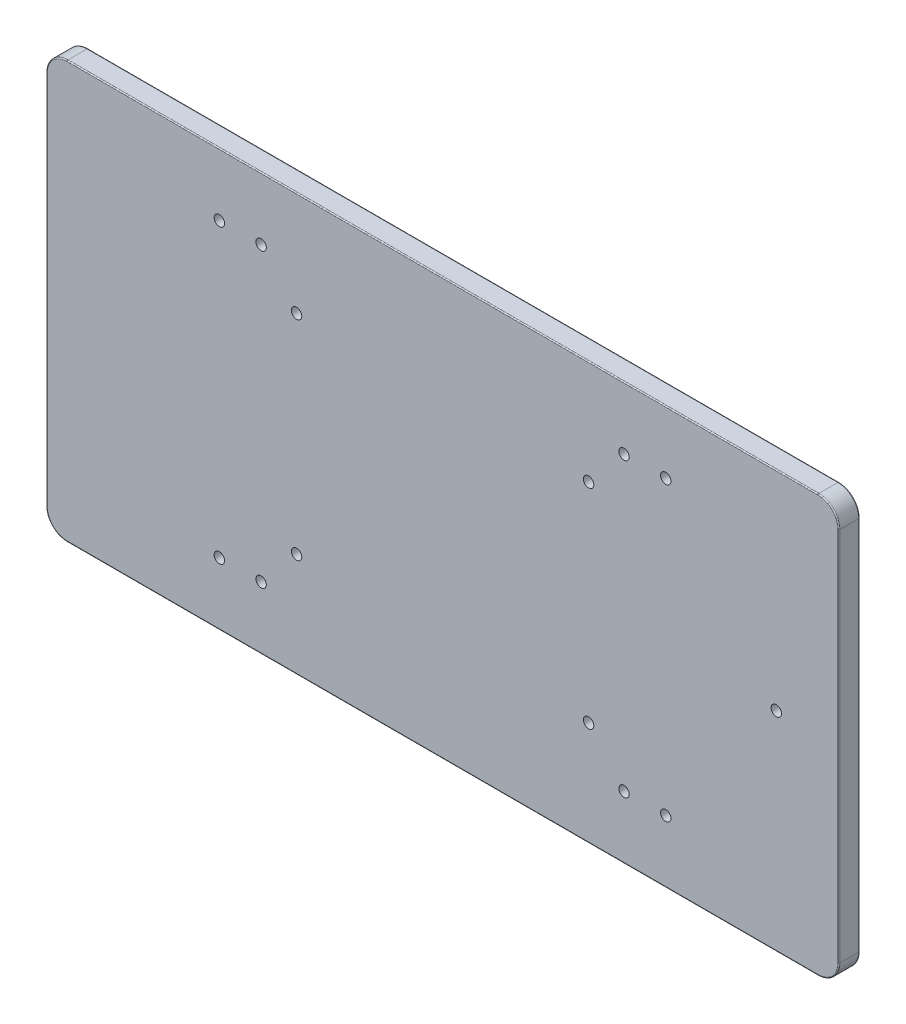
SolidWorks part; units mm, degrees
ref_plane "Front Plane" through (0, 0, 0) normal (0, 0, 1) x (1, 0, 0)
ref_plane "Top Plane" through (0, 0, 0) normal (0, 1, 0) x (1, 0, 0)
ref_plane "Right Plane" through (0, 0, 0) normal (1, 0, 0) x (0, 0, -1)
sketch "Sketch1" plane through (0, 0, 0) normal (0, 0, 1) x (1, 0, 0)
  line L0 (0, 0) -> (30.9738, 0) construction
  line L1 (95, 50) -> (-95, 50)
  line L2 (95, 50) -> (95, -50)
  line L3 (95, -50) -> (-95, -50)
  line L4 (-95, 50) -> (-95, -50)
  line L5 (95, 50) -> (-95, -50) construction
  line L6 (95, -50) -> (-95, 50) construction
  line L7 (-35, 25) -> (35, 25) construction
  line L8 (-35, 25) -> (-35, -25) construction
  line L9 (-35, -25) -> (35, -25) construction
  line L10 (35, 25) -> (35, -25) construction
  line L11 (-35, 25) -> (35, -25) construction
  line L12 (-35, -25) -> (35, 25) construction
  line L13 (30.9738, 0) -> (0, 0) construction
  line L14 (0, 19.8291) -> (0, 0) construction
  line L15 (80, 50) -> (80, -50) construction
  circle A0 centre (-43.5, -35) radius 1.25
  circle A1 centre (-53.5, -35) radius 1.25
  circle A2 centre (-35, -25) radius 1.25
  circle A3 centre (-35, 25) radius 1.25
  circle A4 centre (35, 25) radius 1.25
  circle A5 centre (35, -25) radius 1.25
  circle A6 centre (43.5, -35) radius 1.25
  circle A7 centre (53.5, -35) radius 1.25
  circle A8 centre (53.5, 35) radius 1.25
  circle A9 centre (43.5, 35) radius 1.25
  circle A10 centre (-53.5, 35) radius 1.25
  circle A11 centre (-43.5, 35) radius 1.25
  circle A12 centre (80, 0) radius 1.25
  point P0 (0, 0)
  point P6 (0, 0)
  dimension "D7" = 2.5
  dimension "D10" = 2.5
  dimension "D1" = 190
  dimension "D2" = 100
  dimension "D3" = 50
  dimension "D4" = 70
  dimension "D5" = 43.5
  dimension "D6" = 10
  dimension "D8" = 15
  dimension "D9" = 15
extrude "Boss-Extrude1" add sketch "Sketch1" along normal blind 5
fillet "Fillet1" radius 5 4 edges at (95, 50, 2.5) (95, -50, 2.5) (-95, -50, 2.5) (-95, 50, 2.5)
fillet "Fillet2" radius 0.25 16 edges at (-93.5355, -48.5355, 5) (-95, 0, 5) (-93.5355, 48.5355, 5) (0, 50, 5) (93.5355, 48.5355, 5) (95, 0, 5) (93.5355, -48.5355, 5) (0, -50, 5) (-93.5355, -48.5355, 0) (-95, 0, 0) (-93.5355, 48.5355, 0) (0, 50, 0) (93.5355, 48.5355, 0) (95, 0, 0) (93.5355, -48.5355, 0) (0, -50, 0)
